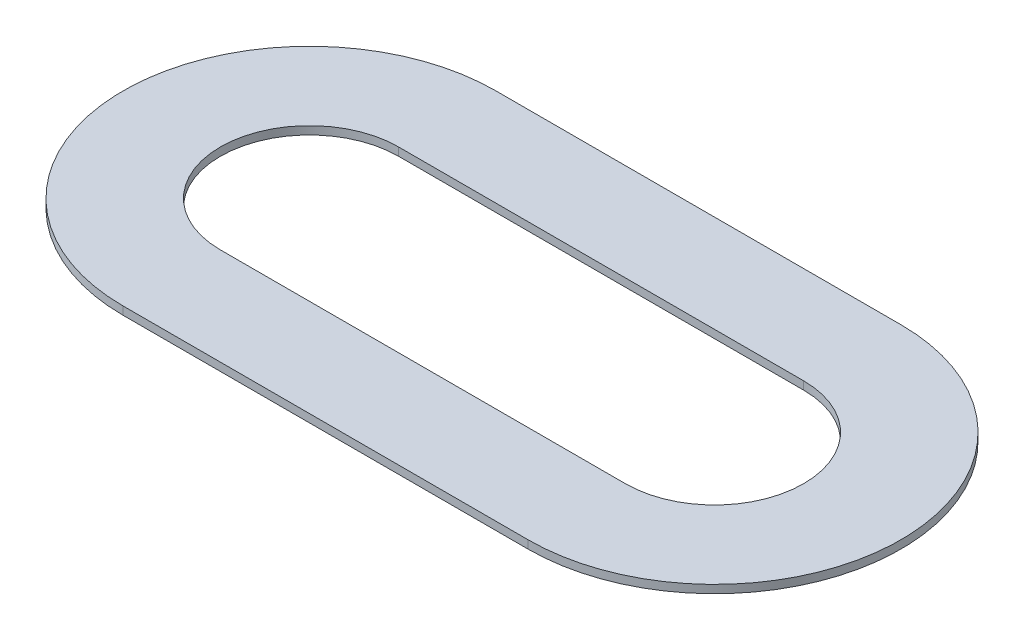
SolidWorks part; units mm, degrees
ref_plane "前视基准面" through (0, 0, 0) normal (0, 0, 1) x (1, 0, 0)
ref_plane "上视基准面" through (0, 0, 0) normal (0, 1, 0) x (1, 0, 0)
ref_plane "右视基准面" through (0, 0, 0) normal (1, 0, 0) x (0, 0, -1)
sketch "草图1" plane through (0, 0, 0) normal (0, 1, 0) x (1, 0, 0)
  line L0 (-250, 110) -> (250, 110)
  line L1 (-250, -110) -> (250, -110)
  line L2 (-250, 230) -> (250, 230)
  line L3 (-250, -230) -> (250, -230)
  arc A0 (-250, 110) -> (-250, -110) centre (-250, 0) ccw
  arc A1 (250, -110) -> (250, 110) centre (250, 0) ccw
  arc A2 (-250, 230) -> (-250, -230) centre (-250, 0) ccw
  arc A3 (250, -230) -> (250, 230) centre (250, 0) ccw
extrude "凸台-拉伸1" add sketch "草图1" along normal blind 10
sketch "草图2" plane through (0, 10, 0) normal (0, 1, 0) x (1, 0, 0)
  line L2 (0, 0) -> (0, 74.0983) construction
  line L3 (-250, 170) -> (250, 170)
  line L4 (-250, -170) -> (250, -170)
  arc A2 (-250, 170) -> (-250, -170) centre (-250, 0) ccw
  arc A3 (250, 170) -> (250, -170) centre (250, 0) cw
  point P4 (-250, 170)
sketch3d "3D草图3"
  line L0 (-250, 10, -170) -> (250, 10, -170) construction
  line L1 (-250, 10, 170) -> (250, 10, 170) construction
  arc A0 (-250, 10, -170) -> (-250, 10, 170) centre (-250, 10, 0) ccw construction
  arc A1 (250, 10, 170) -> (250, 10, -170) centre (250, 10, 0) ccw construction
  spline S0 degree 3 poles (-249.3934, 10, -170) (-83.1311, 10, -170) (83.1311, 10, -170) (249.3934, 10, -170) (249.4608, 10, -170) (249.5956, 10, -170) (249.7978, 10, -170) (249.9326, 10, -170) (250, 10, -170) (250.072, 10, -170) (250.216, 10, -170) (250.432, 10, -169.9995) (250.5759, 10, -169.999) (250.6479, 10, -169.9988) (588.0709, 10, -168.7127) (588.0709, 10, 168.7127) (250.6479, 10, 169.9988) (250.5759, 10, 169.999) (250.432, 10, 169.9995) (250.216, 10, 170) (250.072, 10, 170) (250, 10, 170) (249.9326, 10, 170) (249.7978, 10, 170) (249.5956, 10, 170) (249.4608, 10, 170) (249.3934, 10, 170) (83.1311, 10, 170) (-83.1311, 10, 170) (-249.3934, 10, 170) (-249.4608, 10, 170) (-249.5956, 10, 170) (-249.7978, 10, 170) (-249.9326, 10, 170) (-250, 10, 170) (-250.072, 10, 170) (-250.216, 10, 170) (-250.432, 10, 169.9995) (-250.5759, 10, 169.999) (-250.6479, 10, 169.9988) (-588.0709, 10, 168.7127) (-588.0709, 10, -168.7127) (-250.6479, 10, -169.9988) (-250.5759, 10, -169.999) (-250.432, 10, -169.9995) (-250.216, 10, -170) (-250.072, 10, -170) (-250, 10, -170) (-249.9326, 10, -170) (-249.7978, 10, -170) (-249.5956, 10, -170) (-249.4608, 10, -170) (-249.3934, 10, -170) (-83.1311, 10, -170) (83.1311, 10, -170) knots -0.00012 0 0 0 0.29644 0.29644 0.29644 0.296561 0.296681 0.296801 0.296801 0.296801 0.296929 0.297058 0.297186 0.297186 0.297186 0.499254 0.499254 0.499254 0.499383 0.499511 0.499639 0.499639 0.499639 0.49976 0.49988 0.5 0.5 0.5 0.79644 0.79644 0.79644 0.796561 0.796681 0.796801 0.796801 0.796801 0.796929 0.797058 0.797186 0.797186 0.797186 0.999254 0.999254 0.999254 0.999383 0.999511 0.999639 0.999639 0.999639 0.99976 0.99988 1 1 1 1.29644 1.29644 1.29644 weights 1 1 1 1 1 1 1 1 1 1 1 1 1 1 0.335874 0.335874 1 1 1 1 1 1 1 1 1 1 1 1 1 1 1 1 1 1 1 1 1 1 1 1 0.335874 0.335874 1 1 1 1 1 1 1 1 1 1 1 1 1 only from (-249.3934, 10, -170) to (-249.3934, 10, -170)
  point P2 (-250, 180, 0)
  point P7 (250, 180, 0)
